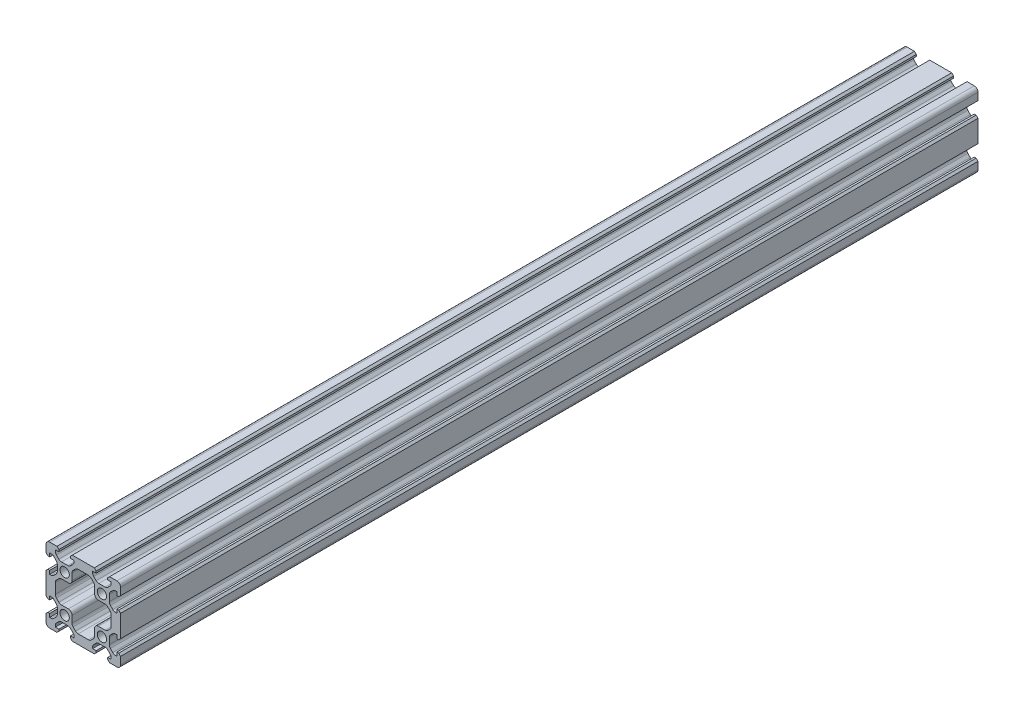
SolidWorks part; units mm, degrees
ref_plane "Front Plane" through (0, 0, 0) normal (0, 0, 1) x (1, 0, 0)
ref_plane "Top Plane" through (0, 0, 0) normal (0, 1, 0) x (1, 0, 0)
ref_plane "Right Plane" through (0, 0, 0) normal (1, 0, 0) x (0, 0, -1)
sketch "Sketch1" plane through (0, 0, 0) normal (0, 0, 1) x (1, 0, 0)
  point P0 (6.9, 0)
  point P1 (0, 6.9)
  point P2 (10, 0)
  point P5 (13.1, 0)
  point P6 (0, 0)
  point P8 (0, 13.1)
  point P9 (-13.1, 0)
  point P14 (0, 0)
  point P15 (0, 0)
  point P19 (0, 0)
  point P21 (10, 0)
  point P22 (10, 0)
  point P23 (6.9, 0)
  point P102 (-6.9, 0)
  line B0 (-4.1716, -14.4142) -> (-5.4621, -13.1236)
  line B1 (-2.7574, -15) -> (2.7574, -15)
  line B2 (-11.7094, -6.0479) -> (-8.0479, -6.0479)
  line B3 (-6.0479, -8.0479) -> (-6.0479, -11.7094)
  line B4 (-13.1236, -5.4621) -> (-14.4142, -4.1716)
  line B5 (-13.1, -19) -> (-14.1, -20)
  line B6 (5.9, -20) -> (-5.9, -20)
  line B7 (-5.9, -20) -> (-6.9, -19)
  line B8 (-14.4142, -15.8284) -> (-13.1236, -14.5379)
  line B9 (-15, -17.2426) -> (-15, -18)
  line B10 (-13.1, -18) -> (-15, -18)
  line B11 (-5, -17.2426) -> (-5, -18)
  line B12 (-5, -18) -> (-6.9, -18)
  line B13 (-6.9, -18) -> (-6.9, -19)
  line B14 (-13.1, -18) -> (-13.1, -19)
  line B15 (-8.2906, -13.9521) -> (-11.7094, -13.9521)
  line B16 (-14.1, -20) -> (-18, -20)
  line B17 (-6.8764, -14.5379) -> (-5.5858, -15.8284)
  line B18 (-19, -6.9) -> (-20, -5.9)
  line B19 (-20, -18) -> (-20, -14.1)
  line B20 (-20, -14.1) -> (-19, -13.1)
  line B21 (-15.8284, -5.5858) -> (-14.5379, -6.8764)
  line B22 (-17.2426, -5) -> (-18, -5)
  line B23 (-18, -6.9) -> (-18, -5)
  line B24 (-17.2426, -15) -> (-18, -15)
  line B25 (-18, -15) -> (-18, -13.1)
  line B26 (-18, -13.1) -> (-19, -13.1)
  line B27 (-18, -6.9) -> (-19, -6.9)
  line B28 (-13.9521, -11.7094) -> (-13.9521, -8.2906)
  line B29 (-14.5379, -13.1236) -> (-15.8284, -14.4142)
  line B30 (-2.7574, 15) -> (2.7574, 15)
  line B31 (-14.4142, 4.1716) -> (-13.1236, 5.4621)
  line B32 (-15, 2.7574) -> (-15, -2.7574)
  line B33 (-6.0479, 11.7094) -> (-6.0479, 8.0479)
  line B34 (-8.0479, 6.0479) -> (-11.7094, 6.0479)
  line B35 (-5.4621, 13.1236) -> (-4.1716, 14.4142)
  line B36 (-19, 13.1) -> (-20, 14.1)
  line B37 (-20, -5.9) -> (-20, 5.9)
  line B38 (-20, 5.9) -> (-19, 6.9)
  line B39 (-15.8284, 14.4142) -> (-14.5379, 13.1236)
  line B40 (-17.2426, 15) -> (-18, 15)
  line B41 (-18, 13.1) -> (-18, 15)
  line B42 (-17.2426, 5) -> (-18, 5)
  line B43 (-18, 5) -> (-18, 6.9)
  line B44 (-18, 6.9) -> (-19, 6.9)
  line B45 (-18, 13.1) -> (-19, 13.1)
  line B46 (-13.9521, 8.2906) -> (-13.9521, 11.7094)
  line B47 (-20, 14.1) -> (-20, 18)
  line B48 (-14.5379, 6.8764) -> (-15.8284, 5.5858)
  line B49 (-6.9, 19) -> (-5.9, 20)
  line B50 (-18, 20) -> (-14.1, 20)
  line B51 (-14.1, 20) -> (-13.1, 19)
  line B52 (-5.5858, 15.8284) -> (-6.8764, 14.5379)
  line B53 (-5, 17.2426) -> (-5, 18)
  line B54 (-6.9, 18) -> (-5, 18)
  line B55 (-15, 17.2426) -> (-15, 18)
  line B56 (-15, 18) -> (-13.1, 18)
  line B57 (-13.1, 18) -> (-13.1, 19)
  line B58 (-6.9, 18) -> (-6.9, 19)
  line B59 (-11.7094, 13.9521) -> (-8.2906, 13.9521)
  line B60 (5.9, 20) -> (-5.9, 20)
  line B61 (-13.1236, 14.5379) -> (-14.4142, 15.8284)
  line B62 (15, 2.7574) -> (15, -2.7574)
  line B63 (4.1716, 14.4142) -> (5.4621, 13.1236)
  line B64 (11.7094, 6.0479) -> (8.0479, 6.0479)
  line B65 (6.0479, 8.0479) -> (6.0479, 11.7094)
  line B66 (13.1236, 5.4621) -> (14.4142, 4.1716)
  line B67 (13.1, 19) -> (14.1, 20)
  line B68 (5.9, 20) -> (6.9, 19)
  line B69 (14.4142, 15.8284) -> (13.1236, 14.5379)
  line B70 (15, 17.2426) -> (15, 18)
  line B71 (13.1, 18) -> (15, 18)
  line B72 (5, 17.2426) -> (5, 18)
  line B73 (5, 18) -> (6.9, 18)
  line B74 (6.9, 18) -> (6.9, 19)
  line B75 (13.1, 18) -> (13.1, 19)
  line B76 (8.2906, 13.9521) -> (11.7094, 13.9521)
  line B77 (14.1, 20) -> (18, 20)
  line B78 (6.8764, 14.5379) -> (5.5858, 15.8284)
  line B79 (19, 6.9) -> (20, 5.9)
  line B80 (20, 18) -> (20, 14.1)
  line B81 (20, 14.1) -> (19, 13.1)
  line B82 (15.8284, 5.5858) -> (14.5379, 6.8764)
  line B83 (17.2426, 5) -> (18, 5)
  line B84 (18, 6.9) -> (18, 5)
  line B85 (17.2426, 15) -> (18, 15)
  line B86 (18, 15) -> (18, 13.1)
  line B87 (18, 13.1) -> (19, 13.1)
  line B88 (18, 6.9) -> (19, 6.9)
  line B89 (13.9521, 11.7094) -> (13.9521, 8.2906)
  line B90 (20, -5.9) -> (20, 5.9)
  line B91 (14.5379, 13.1236) -> (15.8284, 14.4142)
  line B92 (14.4142, -4.1716) -> (13.1236, -5.4621)
  line B93 (6.0479, -11.7094) -> (6.0479, -8.0479)
  line B94 (8.0479, -6.0479) -> (11.7094, -6.0479)
  line B95 (5.4621, -13.1236) -> (4.1716, -14.4142)
  line B96 (19, -13.1) -> (20, -14.1)
  line B97 (20, -5.9) -> (19, -6.9)
  line B98 (15.8284, -14.4142) -> (14.5379, -13.1236)
  line B99 (17.2426, -15) -> (18, -15)
  line B100 (18, -13.1) -> (18, -15)
  line B101 (17.2426, -5) -> (18, -5)
  line B102 (18, -5) -> (18, -6.9)
  line B103 (18, -6.9) -> (19, -6.9)
  line B104 (18, -13.1) -> (19, -13.1)
  line B105 (13.9521, -8.2906) -> (13.9521, -11.7094)
  line B106 (20, -14.1) -> (20, -18)
  line B107 (14.5379, -6.8764) -> (15.8284, -5.5858)
  line B108 (6.9, -19) -> (5.9, -20)
  line B109 (18, -20) -> (14.1, -20)
  line B110 (14.1, -20) -> (13.1, -19)
  line B111 (5.5858, -15.8284) -> (6.8764, -14.5379)
  line B112 (5, -17.2426) -> (5, -18)
  line B113 (6.9, -18) -> (5, -18)
  line B114 (15, -17.2426) -> (15, -18)
  line B115 (15, -18) -> (13.1, -18)
  line B116 (13.1, -18) -> (13.1, -19)
  line B117 (6.9, -18) -> (6.9, -19)
  line B118 (11.7094, -13.9521) -> (8.2906, -13.9521)
  line B119 (13.1236, -14.5379) -> (14.4142, -15.8284)
  circle B120 centre (-10, -10) radius 2.5
  arc B121 (-14.5379, -6.8764) -> (-13.9521, -8.2906) centre (-15.9521, -8.2906) cw
  arc B122 (-15.8284, -5.5858) -> (-17.2426, -5) centre (-17.2426, -7) ccw
  arc B123 (-15, -2.7574) -> (-14.4142, -4.1716) centre (-13, -2.7574) ccw
  arc B124 (6.0479, 8.0479) -> (8.0479, 6.0479) centre (8.0479, 8.0479) ccw
  arc B125 (8.0479, -6.0479) -> (6.0479, -8.0479) centre (8.0479, -8.0479) ccw
  arc B126 (-4.1716, -14.4142) -> (-2.7574, -15) centre (-2.7574, -13) ccw
  arc B127 (-5, -17.2426) -> (-5.5858, -15.8284) centre (-7, -17.2426) ccw
  arc B128 (-14.4142, -15.8284) -> (-15, -17.2426) centre (-13, -17.2426) ccw
  arc B129 (-17.2426, -15) -> (-15.8284, -14.4142) centre (-17.2426, -13) ccw
  arc B130 (-13.9521, -11.7094) -> (-14.5379, -13.1236) centre (-15.9521, -11.7094) cw
  arc B131 (-13.1236, -14.5379) -> (-11.7094, -13.9521) centre (-11.7094, -15.9521) cw
  arc B132 (-8.2906, -13.9521) -> (-6.8764, -14.5379) centre (-8.2906, -15.9521) cw
  arc B133 (-5.4621, -13.1236) -> (-6.0479, -11.7094) centre (-4.0479, -11.7094) cw
  arc B134 (-6.0479, -8.0479) -> (-8.0479, -6.0479) centre (-8.0479, -8.0479) ccw
  arc B135 (-6.0479, 8.0479) -> (-8.0479, 6.0479) centre (-8.0479, 8.0479) cw
  arc B136 (-11.7094, -6.0479) -> (-13.1236, -5.4621) centre (-11.7094, -4.0479) cw
  arc B137 (-18, -20) -> (-20, -18) centre (-18, -18) cw
  circle B138 centre (-10, 10) radius 2.5
  arc B139 (-6.8764, 14.5379) -> (-8.2906, 13.9521) centre (-8.2906, 15.9521) cw
  arc B140 (-5.5858, 15.8284) -> (-5, 17.2426) centre (-7, 17.2426) ccw
  arc B141 (-2.7574, 15) -> (-4.1716, 14.4142) centre (-2.7574, 13) ccw
  arc B142 (-14.4142, 4.1716) -> (-15, 2.7574) centre (-13, 2.7574) ccw
  arc B143 (-17.2426, 5) -> (-15.8284, 5.5858) centre (-17.2426, 7) ccw
  arc B144 (-15.8284, 14.4142) -> (-17.2426, 15) centre (-17.2426, 13) ccw
  arc B145 (-15, 17.2426) -> (-14.4142, 15.8284) centre (-13, 17.2426) ccw
  arc B146 (-11.7094, 13.9521) -> (-13.1236, 14.5379) centre (-11.7094, 15.9521) cw
  arc B147 (-14.5379, 13.1236) -> (-13.9521, 11.7094) centre (-15.9521, 11.7094) cw
  arc B148 (-13.9521, 8.2906) -> (-14.5379, 6.8764) centre (-15.9521, 8.2906) cw
  arc B149 (-13.1236, 5.4621) -> (-11.7094, 6.0479) centre (-11.7094, 4.0479) cw
  arc B150 (-6.0479, 11.7094) -> (-5.4621, 13.1236) centre (-4.0479, 11.7094) cw
  arc B151 (-20, 18) -> (-18, 20) centre (-18, 18) cw
  circle B152 centre (10, 10) radius 2.5
  arc B153 (14.5379, 6.8764) -> (13.9521, 8.2906) centre (15.9521, 8.2906) cw
  arc B154 (15.8284, 5.5858) -> (17.2426, 5) centre (17.2426, 7) ccw
  arc B155 (15, 2.7574) -> (14.4142, 4.1716) centre (13, 2.7574) ccw
  arc B156 (4.1716, 14.4142) -> (2.7574, 15) centre (2.7574, 13) ccw
  arc B157 (5, 17.2426) -> (5.5858, 15.8284) centre (7, 17.2426) ccw
  arc B158 (14.4142, 15.8284) -> (15, 17.2426) centre (13, 17.2426) ccw
  arc B159 (17.2426, 15) -> (15.8284, 14.4142) centre (17.2426, 13) ccw
  arc B160 (13.9521, 11.7094) -> (14.5379, 13.1236) centre (15.9521, 11.7094) cw
  arc B161 (13.1236, 14.5379) -> (11.7094, 13.9521) centre (11.7094, 15.9521) cw
  arc B162 (8.2906, 13.9521) -> (6.8764, 14.5379) centre (8.2906, 15.9521) cw
  arc B163 (5.4621, 13.1236) -> (6.0479, 11.7094) centre (4.0479, 11.7094) cw
  arc B164 (11.7094, 6.0479) -> (13.1236, 5.4621) centre (11.7094, 4.0479) cw
  arc B165 (18, 20) -> (20, 18) centre (18, 18) cw
  circle B166 centre (10, -10) radius 2.5
  arc B167 (6.8764, -14.5379) -> (8.2906, -13.9521) centre (8.2906, -15.9521) cw
  arc B168 (5.5858, -15.8284) -> (5, -17.2426) centre (7, -17.2426) ccw
  arc B169 (2.7574, -15) -> (4.1716, -14.4142) centre (2.7574, -13) ccw
  arc B170 (14.4142, -4.1716) -> (15, -2.7574) centre (13, -2.7574) ccw
  arc B171 (17.2426, -5) -> (15.8284, -5.5858) centre (17.2426, -7) ccw
  arc B172 (15.8284, -14.4142) -> (17.2426, -15) centre (17.2426, -13) ccw
  arc B173 (15, -17.2426) -> (14.4142, -15.8284) centre (13, -17.2426) ccw
  arc B174 (11.7094, -13.9521) -> (13.1236, -14.5379) centre (11.7094, -15.9521) cw
  arc B175 (14.5379, -13.1236) -> (13.9521, -11.7094) centre (15.9521, -11.7094) cw
  arc B176 (13.9521, -8.2906) -> (14.5379, -6.8764) centre (15.9521, -8.2906) cw
  arc B177 (13.1236, -5.4621) -> (11.7094, -6.0479) centre (11.7094, -4.0479) cw
  arc B178 (6.0479, -11.7094) -> (5.4621, -13.1236) centre (4.0479, -11.7094) cw
  arc B179 (20, -18) -> (18, -20) centre (18, -18) cw
sketch_block_instance "4040-1"
sketch_block "4040" parameters "D1"=2, "D2"=2
extrude "Boss-Extrude1" add sketch "Sketch1" along normal blind 460
